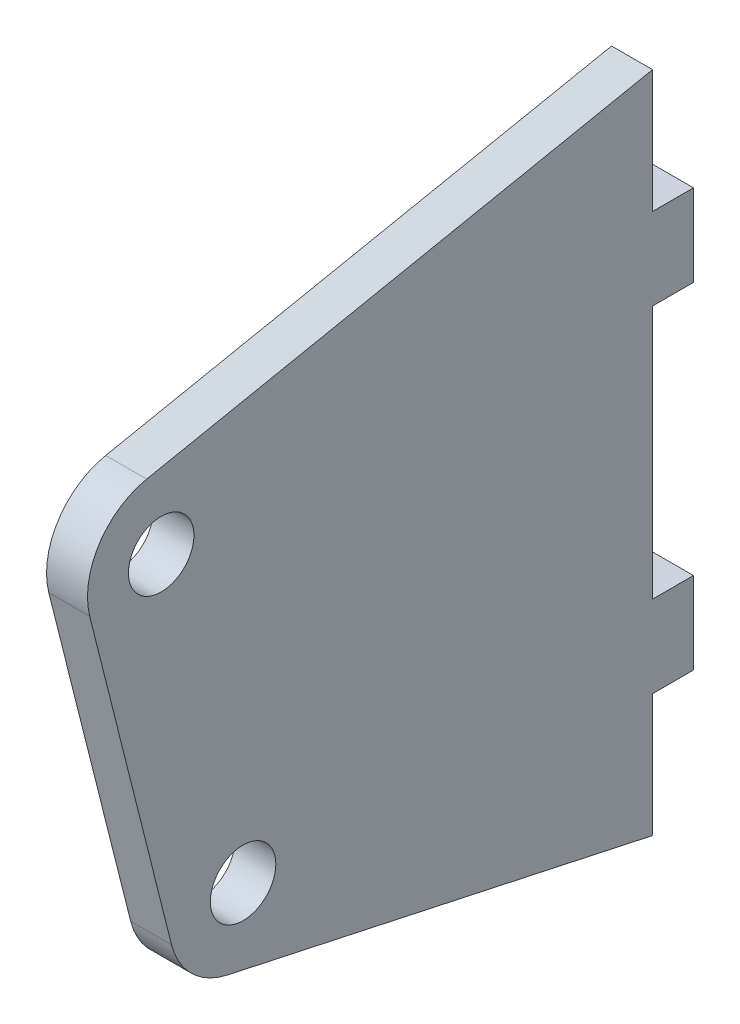
SolidWorks part; units mm, degrees
ref_plane "Front Plane" through (0, 0, 0) normal (1, 0, 0) x (0, 1, 0)
ref_plane "Top Plane" through (0, 0, 0) normal (0, 0, 1) x (0, 1, 0)
ref_plane "Right Plane" through (0, 0, 0) normal (0, 1, 0) x (-1, 0, 0)
sketch "Sketch1" plane through (0, 0, 0) normal (1, 0, 0) x (0, 1, 0)
  line L0 (-40.5, 0) -> (40.5, 0)
  line L1 (-20.5, 0) -> (-20.5, 50) construction
  line L2 (19.2618, 0) -> (19.2618, 60) construction
  line L6 (-20.5, 0) -> (-20.5, -5) construction
  line L7 (-15.5, -5) -> (-25.5, -5)
  line L8 (-25.5, -5) -> (-25.5, 0)
  line L9 (-15.5, -5) -> (-15.5, 0)
  line L10 (19.2618, 0) -> (19.2618, -5) construction
  line L11 (-20.5, 0) -> (20.5, 0) construction
  line L12 (20.5, 0) -> (20.5, -5) construction
  line L13 (25.5, -5) -> (15.5, -5)
  line L14 (15.5, -5) -> (15.5, 0)
  line L15 (25.5, -5) -> (25.5, 0)
  line L16 (-20.5, 50) -> (19.2618, 60) construction
  line L17 (19.2618, 50.7197) -> (21.4569, 51.2718)
  line L18 (-22.6951, 58.7282) -> (17.0667, 68.7282)
  line L19 (-40.5, 0) -> (-29.2974, 51.899)
  line L20 (40.5, 0) -> (28.0854, 61.7733)
  line L22 (-18.3049, 41.2718) -> (19.2618, 50.7197) construction
  line L23 (-18.3049, 41.2718) -> (21.4569, 51.2718) construction
  circle A0 centre (-20.5, 50) radius 4
  circle A1 centre (19.2618, 60) radius 4
  arc A2 (-18.3049, 41.2718) -> (-20.5, 41) centre (-20.5, 50) cw
  arc A3 (28.0854, 61.7733) -> (17.0667, 68.7282) centre (19.2618, 60) ccw
  arc A4 (-29.2974, 51.899) -> (-22.6951, 58.7282) centre (-20.5, 50) cw
  arc A5 (-20.5, 41) -> (-29.2974, 51.899) centre (-20.5, 50) cw construction
  arc A6 (21.4569, 51.2718) -> (28.0854, 61.7733) centre (19.2618, 60) ccw construction
  point P4 (0, 0)
  point P17 (-20.5, -5)
  point P23 (19.2618, -5)
  point P26 (20.5, -5)
  dimension "D6" = 8
  dimension "D7" = 5
  dimension "D1" = 81
  dimension "D2" = 50
  dimension "D3" = 20
  dimension "D4" = 41
  dimension "D5" = 60
  dimension "D8" = 5
  dimension "D9" = 10
  dimension "D10" = 5
  dimension "D11" = 41
  dimension "D12" = 5
  dimension "D13" = 10
extrude "Boss-Extrude1" add sketch "Sketch1" along normal mid plane 5
